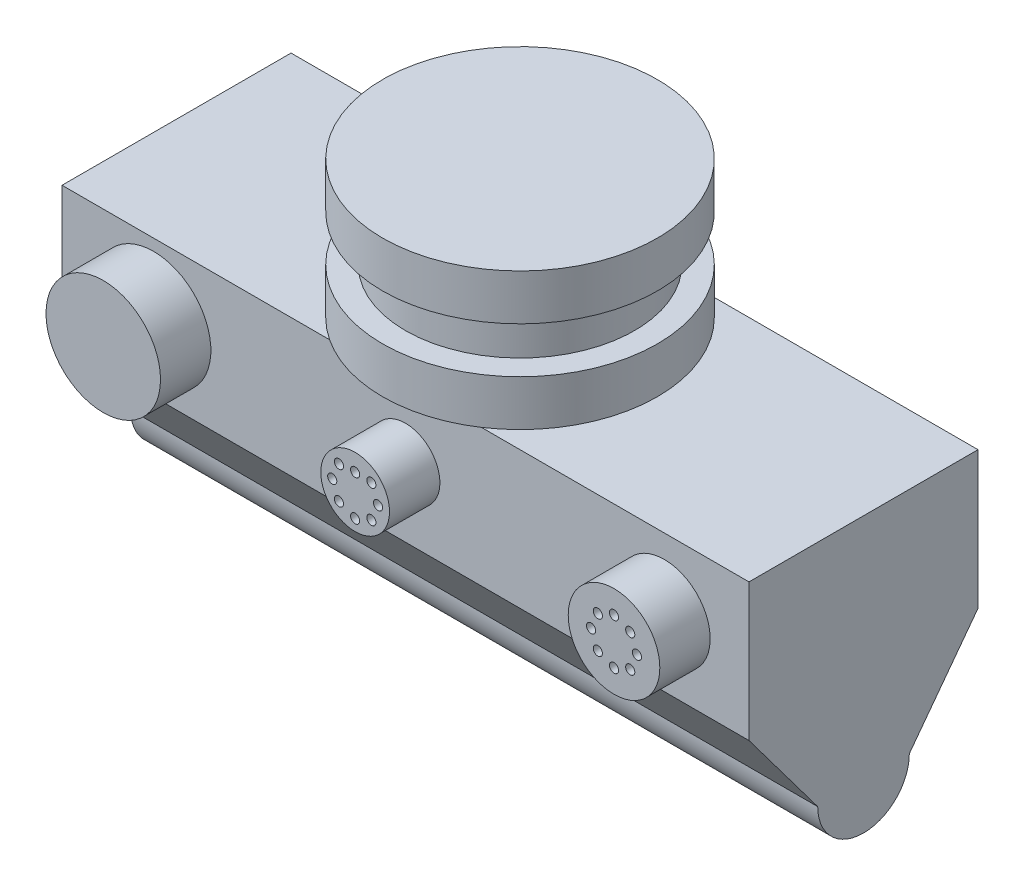
SolidWorks part; units mm, degrees
material "Titan"
ref_plane "Ebene vorne" through (0, 0, 0) normal (0, 0, 1) x (1, 0, 0)
ref_plane "Ebene oben" through (0, 0, 0) normal (0, 1, 0) x (1, 0, 0)
ref_plane "Ebene rechts" through (0, 0, 0) normal (1, 0, 0) x (0, 0, -1)
sketch "Skizze1" plane through (0, 0, 0) normal (0, 1, 0) x (1, 0, 0)
  line L1 (-75, 25) -> (75, 25)
  line L2 (-75, 25) -> (-75, -25)
  line L3 (-75, -25) -> (75, -25)
  line L4 (75, 25) -> (75, -25)
  line L5 (-75, 25) -> (75, -25) construction
  line L6 (-75, -25) -> (75, 25) construction
  point P0 (0, 0)
  dimension "D1" = 50
  dimension "D2" = 150
extrude "Aufsatz-Linear austragen1" add sketch "Skizze1" along normal blind 50
sketch "Skizze2" plane through (75, 0, 0) normal (1, 0, 0) x (0, 0, -1)
  circle A0 centre (0, 0) radius 10
  dimension "D1" = 20
extrude "Aufsatz-Linear austragen2" add sketch "Skizze2" against normal up to surface (150 mm away) up to face at (-75, 25, 0)
sketch "Skizze3" plane through (75, 0, 0) normal (1, 0, 0) x (0, 0, -1)
  line L0 (-10, 0) -> (-25, 20)
  line L1 (-25, 50) -> (-25, 0) construction
  line L2 (-25, 20) -> (-25, 0)
  line L3 (-25, 0) -> (-10, 0)
  line L4 (0, 33) -> (0, -33) construction
  line L5 (25, 20) -> (25, 0)
  line L6 (10, 0) -> (25, 20)
  line L7 (25, 0) -> (10, 0)
  dimension "D1" = 20
extrude "Schnitt-Linear austragen1" cut sketch "Skizze3" against normal blind 182
sketch "Skizze4" plane through (0, 0, 25) normal (0, 0, 1) x (1, 0, 0)
  line L0 (-75, 35) -> (75, 35) construction
  line L1 (-75, 50) -> (-75, 20) construction
  line L2 (75, 50) -> (75, 20) construction
  line L3 (56.5262, 35) -> (56.5262, 45) construction
  line L5 (0, 35) -> (0, 42.5) construction
  circle A0 centre (-55, 35) radius 12.5
  circle A1 centre (56.5262, 35) radius 10
  circle A2 centre (56.5262, 40) radius 1
  circle A3 centre (60.0617, 38.5355) radius 1
  circle A4 centre (61.5262, 35) radius 1
  circle A5 centre (60.0617, 31.4645) radius 1
  circle A6 centre (56.5262, 30) radius 1
  circle A7 centre (52.9907, 31.4645) radius 1
  circle A8 centre (51.5262, 35) radius 1
  circle A9 centre (52.9907, 38.5355) radius 1
  circle A19 centre (0, 35) radius 7.5
  circle A20 centre (0, 38.75) radius 1
  circle A21 centre (3.5355, 38.5355) radius 1
  circle A22 centre (5, 35) radius 1
  circle A23 centre (3.5355, 31.4645) radius 1
  circle A24 centre (0, 30) radius 1
  circle A25 centre (-3.5355, 31.4645) radius 1
  circle A26 centre (-5, 35) radius 1
  circle A27 centre (-3.5355, 38.5355) radius 1
  point P30 (56.5262, 35)
  point P70 (0, 35)
  dimension "D1" = 25
  dimension "D3" = 20
  dimension "D4" = 2
  dimension "D6" = 15
  dimension "D2" = 20
  dimension "D5" = 8
extrude "Aufsatz-Linear austragen3" add sketch "Skizze4" along normal blind 11
sketch "Skizze5" plane through (0, 50, 0) normal (0, 1, 0) x (1, 0, 0)
  circle A0 centre (0, 0) radius 30
  dimension "D1" = 60
extrude "Aufsatz-Linear austragen4" add sketch "Skizze5" along normal blind 30
sketch "Skizze6" plane through (0, 80, 0) normal (0, 1, 0) x (1, 0, 0)
  circle A0 centre (0, 0) radius 30
  circle A1 centre (0, 0) radius 25
  dimension "D1" = 60
  dimension "D2" = 5
extrude "Schnitt-Linear austragen3" cut sketch "Skizze6" against normal blind 10 from offset 10
